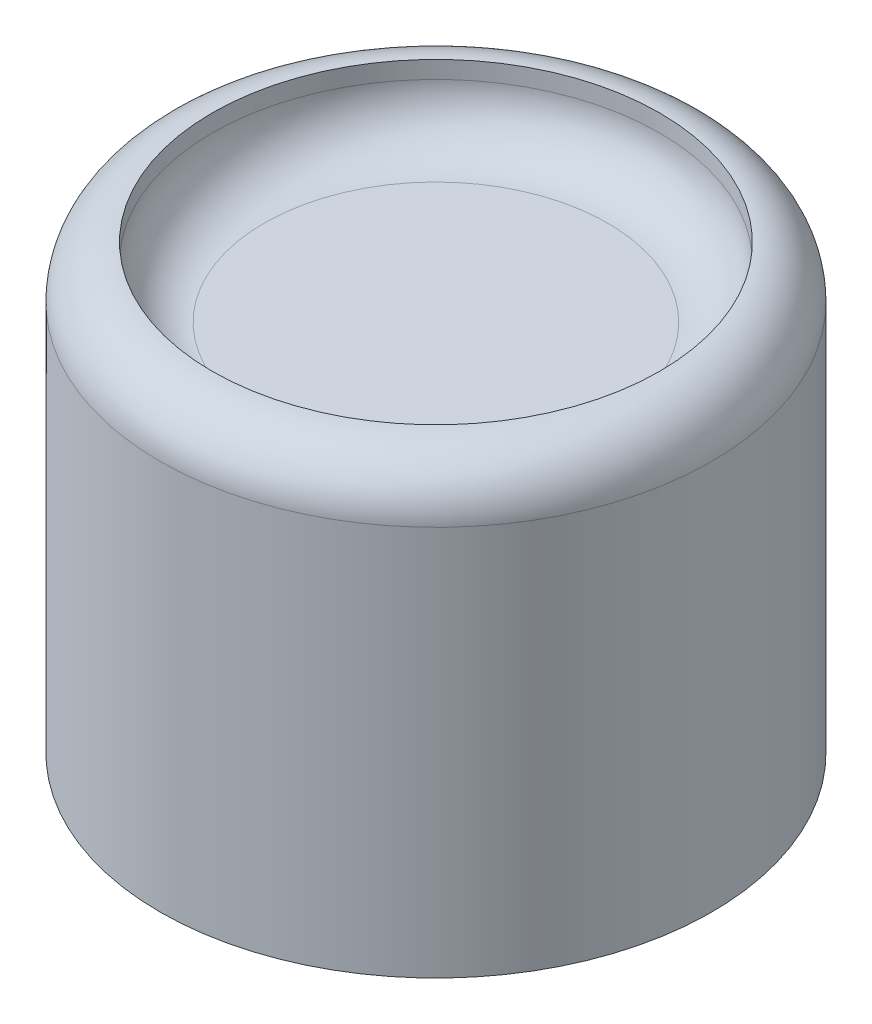
SolidWorks part; units mm, degrees
ref_plane "Front Plane" through (0, 0, 0) normal (0, 0, 1) x (1, 0, 0)
ref_plane "Top Plane" through (0, 0, 0) normal (0, 1, 0) x (1, 0, 0)
ref_plane "Right Plane" through (0, 0, 0) normal (1, 0, 0) x (0, 0, -1)
sketch "Sketch1" plane through (0, 0, 0) normal (0, 1, 0) x (1, 0, 0)
  circle A0 centre (0, 0) radius 7.95
  dimension "D1" = 15.9
extrude "Boss-Extrude1" add sketch "Sketch1" along normal blind 12.75
fillet "Fillet1" radius 1.5 1 edges at (0, 12.75, 7.95)
sketch "Sketch2" plane through (0, 12.75, 0) normal (0, 1, 0) x (1, 0, 0)
  circle A0 centre (0, 0) radius 6.45
extrude "Cut-Extrude1" cut sketch "Sketch2" against normal blind 2
fillet "Fillet2" radius 1.5 1 edges at (0, 10.75, 6.45)
